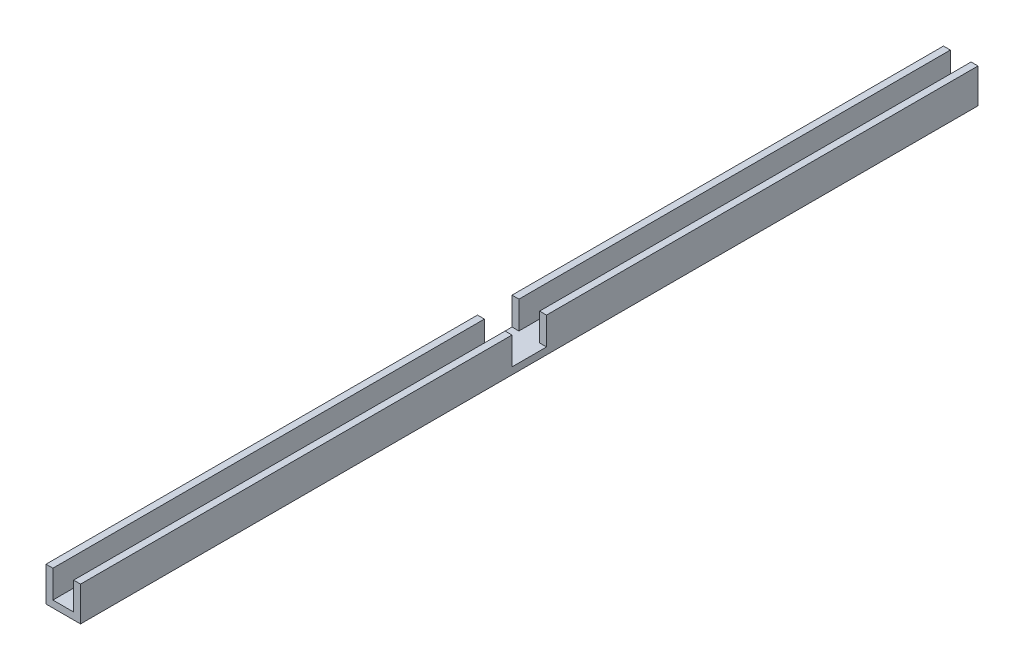
SolidWorks part; units mm, degrees
ref_plane "Plan de face" through (0, 0, 0) normal (0, 0, 1) x (1, 0, 0)
ref_plane "Plan de dessus" through (0, 0, 0) normal (0, 1, 0) x (1, 0, 0)
ref_plane "Plan de droite" through (0, 0, 0) normal (1, 0, 0) x (0, 0, -1)
sketch "Esquisse1" plane through (0, 0, 0) normal (0, 0, 1) x (1, 0, 0)
  line L0 (0, 0) -> (0, -10)
  line L1 (0, -10) -> (10, -10)
  line L2 (10, -10) -> (10, 0)
  line L3 (10, 0) -> (8, 0)
  line L4 (8, 0) -> (8, -8)
  line L5 (8, -8) -> (2, -8)
  line L6 (2, -8) -> (2, 0)
  line L7 (2, 0) -> (0, 0)
  dimension "D1" = 10
  dimension "D2" = 10
  dimension "D3" = 2
  dimension "D4" = 2
  dimension "D5" = 2
extrude "Boss.-Extru.1" add sketch "Esquisse1" along normal blind 260
sketch "Esquisse2" plane through (0, 0, 0) normal (0, 1, 0) x (1, 0, 0)
  line L0 (-8.9962, -125) -> (31.2081, -125)
  line L1 (8, 0) -> (2, 0) construction
  line L2 (-8.9962, -125) -> (-8.9962, -135)
  line L3 (-8.9962, -135) -> (31.2081, -135)
  line L4 (31.2081, -135) -> (31.2081, -127.9846)
  line L5 (31.2081, -125) -> (31.2081, -127.9846)
  dimension "D1" = 125
  dimension "D2" = 10
extrude "Enlèv. mat.-Extru.1" cut sketch "Esquisse2" against normal blind 8
